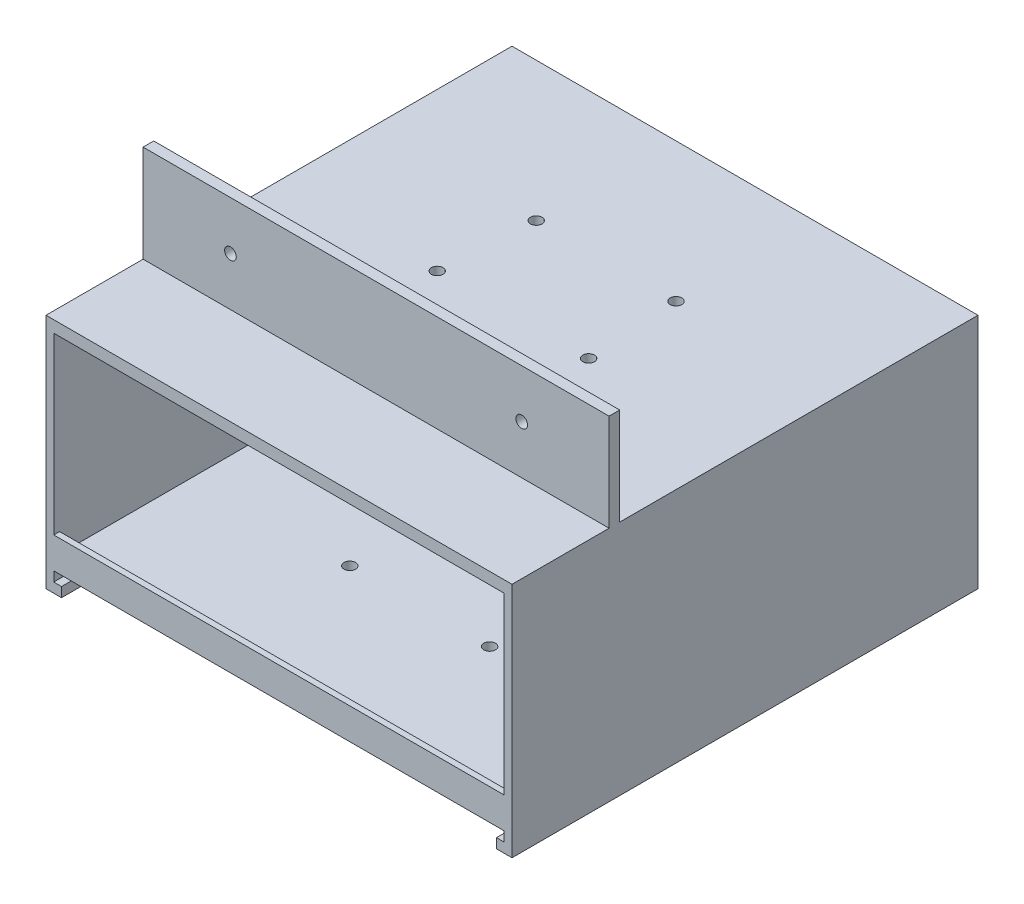
SolidWorks part; units mm, degrees
ref_plane "前视基准面" through (0, 0, 0) normal (0, 0, 1) x (1, 0, 0)
ref_plane "上视基准面" through (0, 0, 0) normal (0, 1, 0) x (1, 0, 0)
ref_plane "右视基准面" through (0, 0, 0) normal (1, 0, 0) x (0, 0, -1)
sketch "草图2" plane through (0, 0, 0) normal (0, 1, 0) x (1, 0, 0)
  line L5 (0, 0) -> (120, 0)
  line L6 (0, 0) -> (0, -120)
  line L7 (0, -120) -> (120, -120)
  line L8 (120, 0) -> (120, -120)
  dimension "D1" = 120
  dimension "D2" = 120
extrude "凸台-拉伸1" add sketch "草图2" along normal blind 3
sketch "草图5" plane through (0, 3, 0) normal (0, 1, 0) x (1, 0, 0)
  line L0 (0, -120) -> (120, -120) construction
  line L1 (0, 0) -> (2, 0)
  line L2 (0, 0) -> (0, -120)
  line L3 (0, -120) -> (2, -120)
  line L4 (2, 0) -> (2, -120)
  line L6 (120, 0) -> (118, 0)
  line L7 (120, 0) -> (120, -120)
  line L8 (120, -120) -> (118, -120)
  line L9 (118, 0) -> (118, -120)
  dimension "D1" = 2
  dimension "D2" = 2
extrude "凸台-拉伸3" add sketch "草图5" along normal blind 50
sketch "草图6" plane through (0, 53, 0) normal (0, 1, 0) x (1, 0, 0)
  line L1 (0, 0) -> (120, 0)
  line L2 (0, 0) -> (0, -120)
  line L3 (0, -120) -> (120, -120)
  line L4 (120, 0) -> (120, -120)
extrude "凸台-拉伸4" add sketch "草图6" along normal blind 3
sketch "草图7" plane through (0, 3, 0) normal (0, 1, 0) x (1, 0, 0)
  line L0 (118, 0) -> (118, -120) construction
  line L1 (2, -120) -> (118, -120)
  line L2 (2, -120) -> (2, -118.5)
  line L3 (2, -118.5) -> (118, -118.5)
  line L4 (118, -120) -> (118, -118.5)
  dimension "D1" = 1.5
extrude "凸台-拉伸5" add sketch "草图7" along normal blind 5
sketch "草图9" plane through (0, 56, 0) normal (0, 1, 0) x (1, 0, 0)
  line L0 (60, -120) -> (60, -95)
  line L1 (0, -120) -> (120, -120) construction
  line L2 (0, 0) -> (0, -120) construction
  line L3 (0, -95) -> (120, -95)
  line L4 (0, -95) -> (0, -92.2648)
  line L5 (0, -92.2648) -> (120, -92.2648)
  line L6 (120, -95) -> (120, -92.2648)
  line L7 (120, -120) -> (120, 0) construction
  dimension "D1" = 25
extrude "凸台-拉伸6" add sketch "草图9" along normal blind 25 contours L5 L6 L3 L4
sketch "草图10" plane through (0, 0, 95) normal (0, 0, 1) x (1, 0, 0)
  line L2 (0, 81) -> (0, 56) construction
  line L3 (120, 81) -> (120, 56) construction
  circle A0 centre (22.5, 68.5) radius 1.5
  circle A1 centre (97.5, 68.5) radius 1.5
  dimension "D1" = 22.5
  dimension "D2" = 22.5
sketch "草图11" plane through (0, 56, 0) normal (0, 1, 0) x (1, 0, 0)
  line L0 (60, 0) -> (60, -84.6886) construction
  line L1 (0, 0) -> (120, 0)
  line L2 (0, 0) -> (0, -92.2648)
  line L3 (0, -92.2648) -> (120, -92.2648)
  line L4 (120, 0) -> (120, -92.2648)
  line L10 (27.5, -27.2648) -> (92.5, -27.2648)
  line L11 (27.5, -27.2648) -> (27.5, -92.2648)
  line L12 (27.5, -92.2648) -> (92.5, -92.2648)
  line L13 (92.5, -27.2648) -> (92.5, -92.2648)
  circle A0 centre (78, -83.7648) radius 1.5
  circle A1 centre (42, -83.7648) radius 1.5
  circle A2 centre (42, -35.7648) radius 1.5
  circle A3 centre (78, -35.7648) radius 1.5
  circle A4 centre (79.5, -59.7648) radius 1.5
  circle A5 centre (40.5, -59.7648) radius 1.5
  dimension "D4" = 3
  dimension "D5" = 3
  dimension "D6" = 3
  dimension "D7" = 3
  dimension "D8" = 3
  dimension "D9" = 3
  dimension "D1" = 65
  dimension "D2" = 65
  dimension "D3" = 32.5
  dimension "D10" = 14.5
  dimension "D11" = 14.5
  dimension "D12" = 14.5
  dimension "D13" = 14.5
  dimension "D14" = 8.5
  dimension "D15" = 8.5
  dimension "D16" = 8.5
  dimension "D17" = 8.5
  dimension "D18" = 13
  dimension "D19" = 13
  dimension "D20" = 32.5
  dimension "D21" = 32.5
extrude "切除-拉伸1" cut sketch "草图11" against normal blind 58 contours A2 | A5 | A1 | A4 | A0 | A3
extrude "切除-拉伸2" cut sketch "草图10" against normal blind 3
sketch "草图13" plane through (0, 0, 0) normal (0, -1, 0) x (-1, 0, 0)
  line L0 (-120, 0) -> (0, 0) construction
  line L1 (0, -120) -> (-4, -120)
  line L2 (0, -120) -> (0, 0)
  line L3 (0, 0) -> (-4, 0)
  line L4 (-4, -120) -> (-4, 0)
  line L6 (-120, -120) -> (-116, -120)
  line L7 (-120, -120) -> (-120, 0)
  line L8 (-120, 0) -> (-116, 0)
  line L9 (-116, -120) -> (-116, 0)
  dimension "D1" = 4
  dimension "D2" = 4
extrude "凸台-拉伸10" add sketch "草图13" along normal blind 5
sketch "草图14" plane through (0, 0, 0) normal (0, 0, -1) x (-1, 0, 0)
  line L1 (-116, 0) -> (-118, 0)
  line L2 (-116, 0) -> (-116, -2.5)
  line L3 (-116, -2.5) -> (-118, -2.5)
  line L4 (-118, 0) -> (-118, -2.5)
  line L5 (-4, 0) -> (-2, 0)
  line L6 (-4, 0) -> (-4, -2.5)
  line L7 (-4, -2.5) -> (-2, -2.5)
  line L8 (-2, 0) -> (-2, -2.5)
  dimension "D1" = 2
  dimension "D2" = 2.5
  dimension "D3" = 2
  dimension "D4" = 2.5
extrude "切除-拉伸3" cut sketch "草图14" against normal blind 120
